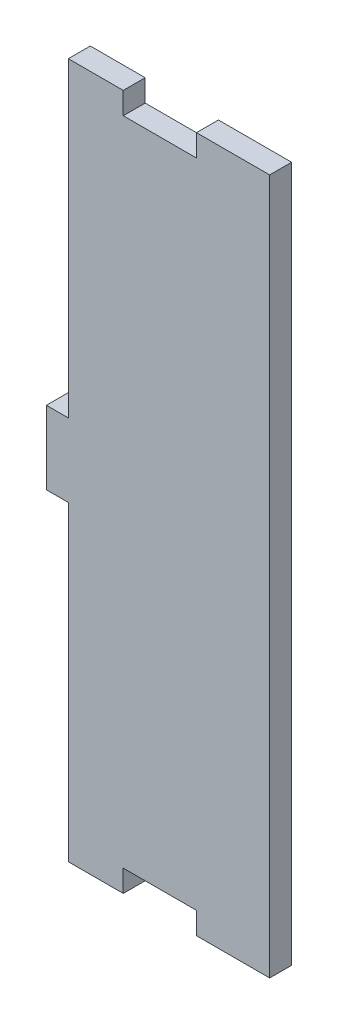
SolidWorks part; units mm, degrees
ref_plane "Front Plane" through (0, 0, 0) normal (0, 0, 1) x (1, 0, 0)
ref_plane "Top Plane" through (0, 0, 0) normal (0, 1, 0) x (1, 0, 0)
ref_plane "Right Plane" through (0, 0, 0) normal (1, 0, 0) x (0, 0, -1)
sketch "Sketch1" plane through (0, 0, 0) normal (0, 0, 1) x (1, 0, 0)
  line L3 (17.5, 47.5) -> (17.5, -2.5)
  line L7 (17.5, -12.5) -> (17.5, -47.5)
  line L14 (-10, 47.5) -> (-10, 5)
  line L15 (0, 0) -> (76.1489, 0) construction
  line L17 (17.5, -47.5) -> (7.5, -47.5)
  line L18 (7.5, -44.5) -> (7.5, -47.5)
  line L19 (-2.5, -44.5) -> (-2.5, -47.5)
  line L20 (-2.5, -44.5) -> (7.5, -44.5)
  line L21 (2.5, 44.5) -> (2.5, 30.4342) construction
  line L30 (-10, -47.5) -> (-2.5, -47.5)
  line L31 (-10, -5) -> (-10, -47.5)
  line L32 (-13, -5) -> (-10, -5)
  line L33 (-13, -5) -> (-13, 5)
  line L34 (-13, 5) -> (-10, 5)
  line L35 (17.5, -2.5) -> (17.5, -12.5)
  line L48 (-10, 47.5) -> (-2.5, 47.5)
  line L49 (7.5, 47.5) -> (17.5, 47.5)
  line L50 (7.5, 47.5) -> (7.5, 44.5)
  line L51 (-2.5, 47.5) -> (-2.5, 44.5)
  line L52 (-2.5, 44.5) -> (7.5, 44.5)
  point P7 (-10, 0)
  dimension "D2" = 10
  dimension "D4" = 10
  dimension "D5" = 50
  dimension "D6" = 35
  dimension "D7" = 10
  dimension "D8" = 17.5
  dimension "D9" = 42.5
  dimension "D10" = 3
extrude "Boss-Extrude1" add sketch "Sketch1" along normal blind 3
sketch "Sketch2" plane through (0, 0, 3) normal (0, 0, 1) x (1, 0, 0)
  line L0 (1.9505, 30.324) -> (11.9505, 30.324) construction
  line L1 (6.9505, 30.324) -> (6.9505, 36.324) construction
  line L3 (8.9505, 42.3257) -> (13.2005, 33.324)
  line L6 (1.9505, 30.324) -> (1.9505, 33.324) construction
  line L7 (1.9505, 30.324) -> (1.9505, 33.324)
  line L8 (1.9505, 33.324) -> (0.7005, 33.324)
  line L9 (4.9505, 42.3257) -> (0.7005, 33.324)
  line L10 (4.9505, 42.3257) -> (4.9505, 30.324)
  line L11 (6.9505, 30.324) -> (6.9505, 25.324) construction
  line L12 (8.9505, 30.324) -> (8.9505, 25.324)
  line L13 (13.2005, 33.324) -> (8.9505, 42.3257) construction
  line L14 (11.9505, 30.324) -> (11.9505, 33.324) construction
  line L15 (8.9505, 42.3257) -> (8.9505, 30.324)
  line L16 (11.9505, 33.324) -> (13.2005, 33.324)
  line L17 (11.9505, 30.324) -> (11.9505, 33.324)
  line L21 (4.9505, 30.324) -> (4.9505, 25.324)
  line L23 (13.9505, 30.324) -> (13.9505, 25.324) construction
  line L24 (15.9505, 30.324) -> (15.9505, 25.324)
  line L25 (11.9505, 30.324) -> (11.9505, 25.324)
  line L26 (-0.0495, 30.324) -> (-0.0495, 25.324) construction
  line L27 (-2.0495, 30.324) -> (-2.0495, 25.324)
  line L28 (1.9505, 30.324) -> (1.9505, 25.324)
  arc A5 (4.9505, 25.324) -> (8.9505, 25.324) centre (6.9505, 25.324) ccw
  arc A7 (11.9505, 25.324) -> (15.9505, 25.324) centre (13.9505, 25.324) ccw
  arc A9 (1.9505, 25.324) -> (-2.0495, 25.324) centre (-0.0495, 25.324) cw
  point P6 (6.9505, 36.324)
  point P11 (6.9505, 27.824)
  point P17 (14.9505, 27.824)
  point P28 (-1.0495, 27.824)
  dimension "D1" = 3
  dimension "D4" = 2
  dimension "D6" = 1.25
  dimension "D7" = 2
  dimension "D8" = 2
  dimension "D2" = 4
  dimension "D3" = 10
  dimension "D5" = 2
  dimension "D10" = 5
sketch "Sketch3" plane through (0, 0, -53) normal (0, 0, -1) x (-1, 0, 0)
  line L0 (-9.7815, 28.1572) -> (0.2185, 28.1572) construction
  line L1 (-4.7815, 28.1572) -> (-4.7815, 34.1572) construction
  line L3 (-2.7815, 40.1589) -> (1.4685, 31.1572)
  line L6 (-9.7815, 28.1572) -> (-9.7815, 31.1572) construction
  line L7 (-9.7815, 28.1572) -> (-9.7815, 31.1572)
  line L8 (-9.7815, 31.1572) -> (-11.0315, 31.1572)
  line L9 (-6.7815, 40.1589) -> (-11.0315, 31.1572)
  line L10 (-6.7815, 40.1589) -> (-6.7815, 28.1572)
  line L11 (-4.7815, 28.1572) -> (-4.7815, 23.1572) construction
  line L12 (-2.7815, 28.1572) -> (-2.7815, 23.1572)
  line L13 (1.4685, 31.1572) -> (-2.7815, 40.1589) construction
  line L14 (0.2185, 28.1572) -> (0.2185, 31.1572) construction
  line L15 (-2.7815, 40.1589) -> (-2.7815, 28.1572)
  line L16 (0.2185, 31.1572) -> (1.4685, 31.1572)
  line L17 (0.2185, 28.1572) -> (0.2185, 31.1572)
  line L21 (-6.7815, 28.1572) -> (-6.7815, 23.1572)
  line L23 (2.2185, 28.1572) -> (2.2185, 23.1572) construction
  line L24 (4.2185, 28.1572) -> (4.2185, 23.1572)
  line L25 (0.2185, 28.1572) -> (0.2185, 23.1572)
  line L26 (-11.7815, 28.1572) -> (-11.7815, 23.1572) construction
  line L27 (-13.7815, 28.1572) -> (-13.7815, 23.1572)
  line L28 (-9.7815, 28.1572) -> (-9.7815, 23.1572)
  arc A5 (-6.7815, 23.1572) -> (-2.7815, 23.1572) centre (-4.7815, 23.1572) ccw
  arc A7 (0.2185, 23.1572) -> (4.2185, 23.1572) centre (2.2185, 23.1572) ccw
  arc A9 (-9.7815, 23.1572) -> (-13.7815, 23.1572) centre (-11.7815, 23.1572) cw
  point P6 (-4.7815, 34.1572)
  point P11 (-4.7815, 25.6572)
  point P17 (3.2185, 25.6572)
  point P28 (-12.7815, 25.6572)
  dimension "D1" = 3
  dimension "D4" = 2
  dimension "D6" = 1.25
  dimension "D7" = 2
  dimension "D8" = 2
  dimension "D2" = 4
  dimension "D3" = 10
  dimension "D5" = 2
  dimension "D10" = 5
